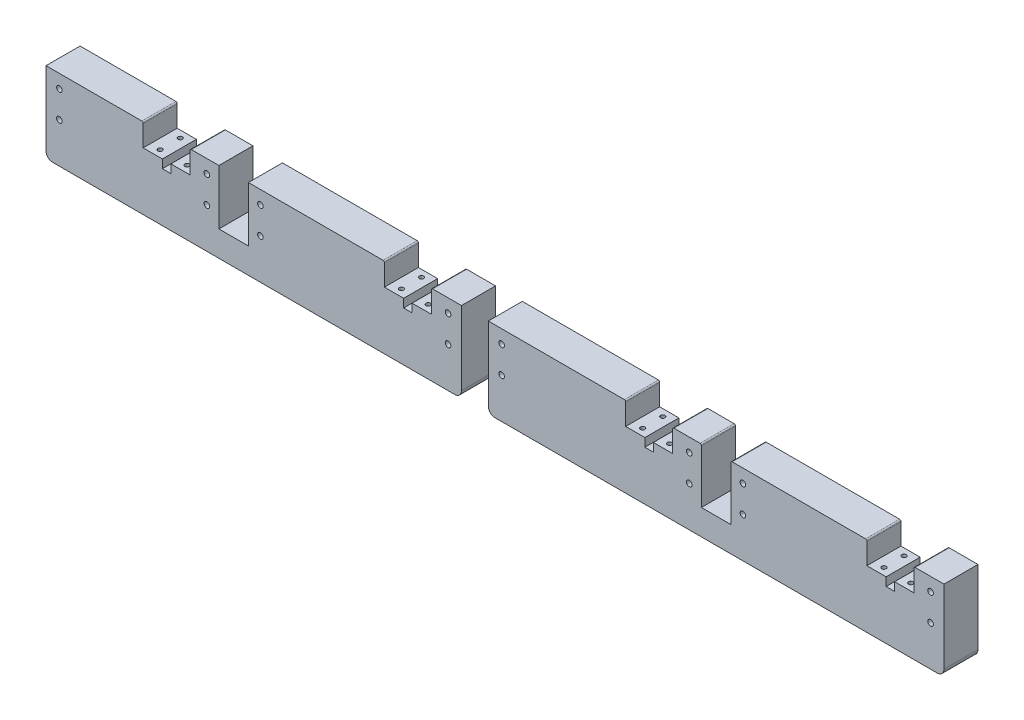
SolidWorks part; units mm, degrees
material "6061-T6 (SS)"
ref_plane "Front Plane" through (0, 0, 0) normal (0, 0, 1) x (1, 0, 0)
ref_plane "Top Plane" through (0, 0, 0) normal (0, 1, 0) x (1, 0, 0)
ref_plane "Right Plane" through (0, 0, 0) normal (1, 0, 0) x (0, 0, -1)
sketch "Sketch1" plane through (0, 0, 0) normal (0, 0, 1) x (1, 0, 0)
  line L0 (-70, 30) -> (-70, 10) construction
  line L1 (-80, 40) -> (80, 40)
  line L2 (-80, 40) -> (-80, 0)
  line L3 (-80, 0) -> (80, 0)
  line L4 (80, 40) -> (80, 0)
  line L9 (36.825, 23.175) -> (43.175, 23.175) construction
  line L10 (36.825, 23.175) -> (36.825, 16.825) construction
  line L11 (36.825, 16.825) -> (43.175, 16.825) construction
  line L12 (43.175, 23.175) -> (43.175, 16.825) construction
  line L13 (0, 0) -> (0, 40) construction
  line L14 (36.825, 20) -> (43.175, 20) construction
  line L15 (40, 16.825) -> (40, 23.175) construction
  line L16 (22.5, 40) -> (22.5, 23.125)
  line L17 (22.5, 40) -> (57.5, 40) construction
  line L18 (22.5, 40) -> (22.5, 23.175) construction
  line L19 (22.5, 23.175) -> (57.5, 23.175) construction
  line L20 (57.5, 40) -> (57.5, 23.175) construction
  line L21 (22.5, 23.125) -> (36.825, 23.125)
  line L22 (36.825, 23.125) -> (36.825, 16.825)
  line L23 (36.825, 16.825) -> (43.175, 16.825)
  line L24 (43.175, 16.825) -> (43.175, 23.125)
  line L25 (43.175, 23.125) -> (57.5, 23.125)
  line L26 (57.5, 23.125) -> (57.5, 40)
  line L27 (-260, 40) -> (-260, 0)
  line L28 (-80, 40) -> (-100, 40)
  line L29 (-80, 40) -> (-80, 0)
  line L30 (-80, 0) -> (-100, 0)
  line L31 (-100, 40) -> (-100, 0)
  line L32 (-260, 40) -> (-280, 40)
  line L33 (-280, 40) -> (-280, 0)
  line L34 (-260, 0) -> (-280, 0)
  line L35 (-260, 40) -> (-260, 0)
  line L36 (-260, 40) -> (-100, 40)
  line L37 (-100, 40) -> (-100, 0)
  line L38 (-260, 0) -> (-100, 0)
  line L39 (-122.5, 23.125) -> (-122.5, 40)
  line L40 (-136.825, 23.125) -> (-122.5, 23.125)
  line L41 (-136.825, 16.825) -> (-136.825, 23.125)
  line L42 (-143.175, 16.825) -> (-136.825, 16.825)
  line L43 (-143.175, 23.125) -> (-143.175, 16.825)
  line L44 (-157.5, 23.125) -> (-143.175, 23.125)
  line L45 (-157.5, 40) -> (-157.5, 23.125)
  line L46 (-440, 40) -> (-440, 0)
  line L47 (-440, 40) -> (-460, 40)
  line L48 (-460, 40) -> (-460, 0)
  line L49 (-440, 0) -> (-460, 0)
  line L50 (-440, 40) -> (-440, 0)
  line L51 (-440, 40) -> (-280, 40)
  line L52 (-280, 40) -> (-280, 0)
  line L53 (-440, 0) -> (-280, 0)
  line L54 (-302.5, 23.125) -> (-302.5, 40)
  line L55 (-316.825, 23.125) -> (-302.5, 23.125)
  line L56 (-316.825, 16.825) -> (-316.825, 23.125)
  line L57 (-323.175, 16.825) -> (-316.825, 16.825)
  line L58 (-323.175, 23.125) -> (-323.175, 16.825)
  line L59 (-337.5, 23.125) -> (-323.175, 23.125)
  line L60 (-337.5, 40) -> (-337.5, 23.125)
  line L61 (-620, 40) -> (-620, 0)
  line L62 (-620, 40) -> (-640, 40)
  line L63 (-640, 40) -> (-640, 0)
  line L64 (-620, 0) -> (-640, 0)
  line L65 (-620, 40) -> (-620, 0)
  line L66 (-620, 40) -> (-460, 40)
  line L67 (-460, 40) -> (-460, 0)
  line L68 (-620, 0) -> (-460, 0)
  line L69 (-482.5, 23.125) -> (-482.5, 40)
  line L70 (-496.825, 23.125) -> (-482.5, 23.125)
  line L71 (-496.825, 16.825) -> (-496.825, 23.125)
  line L72 (-503.175, 16.825) -> (-496.825, 16.825)
  line L73 (-503.175, 23.125) -> (-503.175, 16.825)
  line L74 (-517.5, 23.125) -> (-503.175, 23.125)
  line L75 (-517.5, 40) -> (-517.5, 23.125)
  line L76 (-302.5, 40) -> (-302.5, 50)
  line L77 (-640, 0) -> (80, 0)
  line L78 (-640, 0) -> (-640, -20)
  line L79 (-640, -20) -> (80, -20)
  line L80 (80, 0) -> (80, -20)
  line L81 (-122.5, 40) -> (22.5, 40)
  line L82 (-122.5, 40) -> (-122.5, 50)
  line L83 (-122.5, 50) -> (22.5, 50)
  line L84 (22.5, 40) -> (22.5, 50)
  line L85 (80, 40) -> (57.5, 40)
  line L86 (80, 40) -> (80, 50)
  line L87 (80, 50) -> (57.5, 50)
  line L88 (57.5, 40) -> (57.5, 50)
  line L89 (-302.5, 40) -> (-157.5, 40)
  line L90 (-157.5, 40) -> (-157.5, 50)
  line L91 (-302.5, 50) -> (-157.5, 50)
  line L92 (-482.5, 40) -> (-482.5, 50)
  line L93 (-482.5, 40) -> (-337.5, 40)
  line L94 (-337.5, 40) -> (-337.5, 50)
  line L95 (-482.5, 50) -> (-337.5, 50)
  line L100 (-662.5, 40) -> (-662.5, 50) [skipped]
  line L101 (-662.5, 50) -> (-517.5, 50) [skipped]
  line L102 (-517.5, 40) -> (-517.5, 50) [skipped]
  line L103 (-662.5, 40) -> (-517.5, 40) [skipped]
  line L105 (-640, 40) -> (-517.5, 40)
  line L106 (-640, 40) -> (-640, 50)
  line L107 (-640, 50) -> (-517.5, 50)
  line L108 (-517.5, 40) -> (-517.5, 50)
  circle A0 centre (-70, 30) radius 2.5 construction
  circle A1 centre (-70, 10) radius 2.5 construction
  circle A2 centre (70, 10) radius 2.5 construction
  circle A3 centre (70, 30) radius 2.5 construction
  circle A4 centre (-110, 30) radius 2.5 construction
  circle A5 centre (-110, 10) radius 2.5 construction
  circle A6 centre (-250, 30) radius 2.5 construction
  circle A7 centre (-250, 10) radius 2.5 construction
  circle A8 centre (-290, 30) radius 2.5 construction
  circle A9 centre (-290, 10) radius 2.5 construction
  circle A10 centre (-430, 30) radius 2.5 construction
  circle A11 centre (-430, 10) radius 2.5 construction
  circle A12 centre (-470, 30) radius 2.5 construction
  circle A13 centre (-470, 10) radius 2.5 construction
  circle A14 centre (-610, 30) radius 2.5 construction
  circle A15 centre (-610, 10) radius 2.5 construction
  point P10 (0, 0)
  point P15 (80, 20)
  point P31 (40, 23.175)
  dimension "D8" = 5
  dimension "D10" = 10
  dimension "D3" = 20
  dimension "D7" = 10
  dimension "D2" = 160
  dimension "D4" = 40
  dimension "D5" = 35
  dimension "D6" = 6.35
  dimension "D9" = 40
  dimension "D11" = 0.05
  dimension "D12" = 20
  dimension "D14" = 180
  dimension "D15" = 20
  dimension "D16" = 10
  dimension "D18" = 180
  dimension "D13" = 4
  dimension "D17" = 4
extrude "Boss-Extrude1" add sketch "Sketch1" against normal blind 25.4
sketch "Sketch8" plane through (0, 23.125, 0) normal (0, 1, 0) x (1, 0, 0)
  line L8 (36.825, 0) -> (22.5, 0) construction
  line L9 (22.5, 0) -> (22.5, 25.4) construction
  line L10 (22.5, 25.4) -> (36.825, 25.4) construction
  line L11 (36.825, 25.4) -> (36.825, 0) construction
  line L12 (57.5, 0) -> (43.175, 0) construction
  line L13 (43.175, 0) -> (43.175, 25.4) construction
  line L14 (43.175, 25.4) -> (57.5, 25.4) construction
  line L15 (57.5, 25.4) -> (57.5, 0) construction
  line L16 (30, 5.2) -> (50, 5.2) construction
  line L17 (36.825, 25.4) -> (43.175, 25.4)
  line L18 (36.825, 25.4) -> (36.825, 0) construction
  line L19 (36.825, 25.4) -> (36.825, 0) construction
  line L20 (30, 5.2) -> (30, 20.2) construction
  line L21 (30, 20.2) -> (50, 20.2) construction
  line L22 (50, 20.2) -> (50, 5.2) construction
  circle A0 centre (50, 5.2) radius 2 construction
  circle A1 centre (30, 5.2) radius 2 construction
  circle A2 centre (30, 20.2) radius 2 construction
  circle A3 centre (50, 20.2) radius 2 construction
  point P4 (40, 5.2)
  point P5 (40, 25.4)
  point P17 (50, 12.7)
  point P18 (43.175, 12.7)
  dimension "D1" = 4
  dimension "D2" = 20
  dimension "D3" = 15
hole_wizard "Tap Drill for M4x0.7 Tap1" positions "3DSketch3" profile "Sketch9" hole size "M4x0.7" standard "ANSI Metric"
sketch3d "3DSketch3"
  point P10 (30, 23.125, -5.2)
  point P12 (50, 23.125, -5.2)
  point P19 (30, 23.125, -20.2)
  point P21 (50, 23.125, -20.2)
sketch "Sketch9" plane through (30, 23.125, -5.2) normal (1, 0, 0) x (0, 0, 1)
  line L0 (0, 0) -> (0, 5.9914)
  line L1 (0, 5.9914) -> (1.65, 5)
  line L2 (1.65, 5) -> (1.65, 0)
  line L5 (1.65, 0) -> (0, 0)
  line L10 (0, 5.9914) -> (-1.65, 5) construction
  line L11 (0, -6.35) -> (0, 107.95) construction
  dimension "Hole Dia." = 3.3
  dimension "Hole Depth" = 5
  dimension "Drill Angle" = 118
hole_wizard "Tap Drill for M5x0.8 Tap3" positions "3DSketch4" profile "Sketch10" hole size "M5x0.8" standard "ANSI Metric" end condition up to next
sketch3d "3DSketch4"
  point P0 (-70, 30, 0)
  point P2 (-70, 10, 0)
  point P4 (70, 10, 0)
  point P6 (70, 30, 0)
sketch "Sketch10" plane through (-70, 30, 0) normal (1, 0, 0) x (0, -1, 0)
  line L0 (0, 0) -> (0, 25.4)
  line L1 (0, 25.4) -> (2.1, 25.4)
  line L2 (2.1, 25.4) -> (2.1, 0)
  line L5 (2.1, 0) -> (0, 0)
  line L11 (0, -6.35) -> (0, 107.95) construction
  dimension "Thru Hole Dia." = 4.2
  dimension "Thru Hole Depth" = 25.4
ref_plane "Plane1" through (0, 0, -12.7) normal (0, 0, -1) x (-1, 0, 0)
pattern_linear "LPattern5" count 4 spacing 180 along (-1, 0, 0) of "Tap Drill for M4x0.7 Tap1", "Tap Drill for M5x0.8 Tap3"
sketch "Sketch11" plane through (0, 0, 0) normal (0, 0, 1) x (1, 0, 0)
  line L0 (-110, 30) -> (-70, 30) construction
  line L1 (-101, 41) -> (-79, 41)
  line L2 (-101, 41) -> (-101, -1)
  line L3 (-101, -1) -> (-79, -1)
  line L4 (-79, 41) -> (-79, -1)
  line L5 (-110, 10) -> (-70, 10) construction
  line L6 (-110, 30) -> (-110, 10) construction
  line L7 (-70, 30) -> (-70, 10) construction
  line L8 (-281, 41) -> (-281, -1)
  line L9 (-281, 41) -> (-259, 41)
  line L10 (-259, 41) -> (-259, -1)
  line L11 (-281, -1) -> (-259, -1)
  line L12 (-461, 41) -> (-461, -1)
  line L13 (-461, 41) -> (-439, 41)
  line L14 (-439, 41) -> (-439, -1)
  line L15 (-461, -1) -> (-439, -1)
  line L16 (-640, -20) -> (80, -20) construction
  line L17 (-640, 40) -> (-590, 40)
  line L18 (-640, 40) -> (-640, -20)
  line L19 (-640, -20) -> (-590, -20)
  line L20 (-590, 40) -> (-590, -20)
  line L21 (-517.5, 40) -> (-640, 40) construction
  circle A0 centre (-580, 30) radius 2.1
  circle A1 centre (-580, 10) radius 2.1
  circle A2 centre (70, 30) radius 2.1 construction
  point P12 (-90, 30)
  point P13 (-90, 41)
  point P14 (-70, 20)
  point P15 (-79, 20)
  dimension "D6" = 10
  dimension "D1" = 22
  dimension "D2" = 42
  dimension "D4" = 180
  dimension "D5" = 50
  dimension "D3" = 3
extrude "Cut-Extrude1" cut sketch "Sketch11" against normal up to next contours L20 L17 L18 L19 | A0 | A1 | L4 L1 L2 L3 | L12 L15 L14 L13
sketch "Sketch13" plane through (0, 0, 0) normal (0, 0, 1) x (1, 0, 0)
  line L0 (-290, 30) -> (-250, 30) construction
  line L1 (-590, -20) -> (80, -20) construction
  line L2 (-280, 40) -> (-260, 40)
  line L3 (-280, 40) -> (-280, -20)
  line L4 (-280, -20) -> (-260, -20)
  line L5 (-260, 40) -> (-260, -20)
  line L7 (-302.5, 40) -> (-157.5, 40) construction
  point P8 (-270, 40)
  point P9 (-270, 30)
  dimension "D1" = 20
extrude "Cut-Extrude3" cut sketch "Sketch13" against normal up to next contours L3 L0 L5 L2 | L0 L3 L4 L5
fillet "Fillet1" radius 1 6 edges at (-101, 40, -12.7) (-79, 40, -12.7) (57.5, 40, -12.7) (-157.5, 40, -12.7) (-122.5, 40, -12.7) (22.5, 40, -12.7)
fillet "Fillet4" radius 1 4 edges at (-517.5, 40, -12.7) (-482.5, 40, -12.7) (-337.5, 40, -12.7) (-302.5, 40, -12.7)
fillet "Fillet2" radius 5 2 edges at (80, -20, -12.7) (-260, -20, -12.7)
fillet "Fillet3" radius 5 2 edges at (-590, -20, -12.7) (-280, -20, -12.7)
